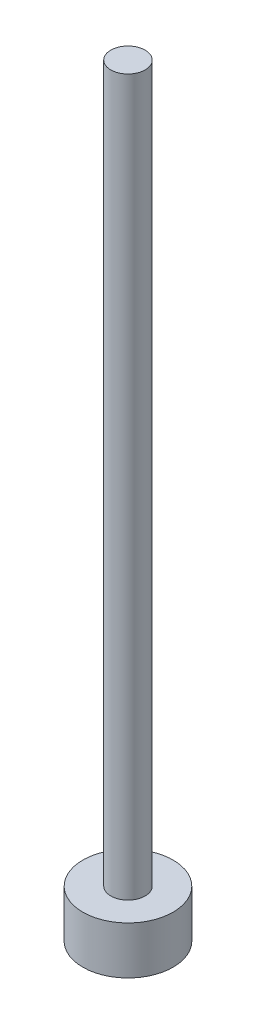
SolidWorks part; units mm, degrees
ref_plane "Front Plane" through (0, 0, 0) normal (0, 0, 1) x (1, 0, 0)
ref_plane "Top Plane" through (0, 0, 0) normal (0, 1, 0) x (1, 0, 0)
ref_plane "Right Plane" through (0, 0, 0) normal (1, 0, 0) x (0, 0, -1)
sketch "Sketch1" plane through (0, 0, 0) normal (0, 1, 0) x (1, 0, 0)
  circle A0 centre (0, 0) radius 2.84
  dimension "D1" = 5.68
extrude "Boss-Extrude1" add sketch "Sketch1" along normal blind 3
sketch "Sketch2" plane through (0, 3, 0) normal (0, 1, 0) x (1, 0, 0)
  circle A0 centre (0, 0) radius 1.0797
extrude "Boss-Extrude2" add sketch "Sketch2" along normal blind 45
sketch "Sketch3" plane through (0, 0, 0) normal (0, -1, 0) x (1, 0, 0)
  line L0 (0, 2.84) -> (0, -2.84) construction
  line L2 (1.6512, 0) -> (0.8256, 1.43)
  line L3 (0.8256, 1.43) -> (-0.8256, 1.43)
  line L4 (-0.8256, 1.43) -> (-1.6512, 0)
  line L5 (-1.6512, 0) -> (-0.8256, -1.43)
  line L6 (-0.8256, -1.43) -> (0.8256, -1.43)
  line L7 (0.8256, -1.43) -> (1.6512, 0)
  circle A0 centre (0, 0) radius 2.84 construction
  circle A1 centre (0, 0) radius 1.43 construction
  dimension "D1" = 2.86
extrude "Cut-Extrude1" cut sketch "Sketch3" against normal blind 1.4
